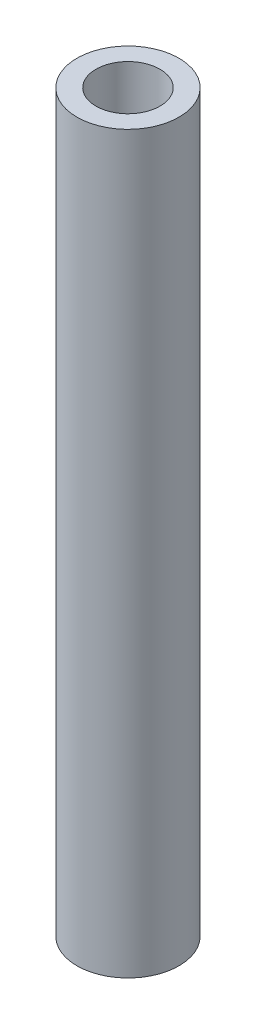
SolidWorks part; units mm, degrees
ref_plane "Front Plane" through (0, 0, 0) normal (0, 0, 1) x (1, 0, 0)
ref_plane "Top Plane" through (0, 0, 0) normal (0, 1, 0) x (1, 0, 0)
ref_plane "Right Plane" through (0, 0, 0) normal (1, 0, 0) x (0, 0, -1)
sketch "Sketch1" plane through (0, 0, 0) normal (0, 1, 0) x (1, 0, 0)
  circle A0 centre (0, 0) radius 3.9688
  circle A1 centre (0, 0) radius 2.4892
  dimension "D1" = 7.9375
  dimension "D2" = 4.9784
extrude "Boss-Extrude2" add sketch "Sketch1" along normal mid plane 57.15
